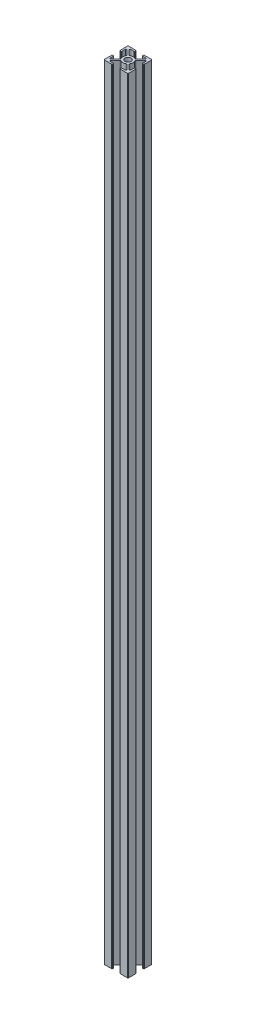
SolidWorks part; units mm, degrees
ref_plane "Front Plane" through (0, 0, 0) normal (0, 0, 1) x (1, 0, 0)
ref_plane "Top Plane" through (0, 0, 0) normal (0, 1, 0) x (1, 0, 0)
ref_plane "Right Plane" through (0, 0, 0) normal (1, 0, 0) x (0, 0, -1)
sketch "Sketch1" plane through (0, 0, 0) normal (0, 1, 0) x (1, 0, 0)
  point P0 (0, 0)
  line B0 (-6.2474, 8.6) -> (-3.6, 8.6)
  line B1 (-9.5, -10) -> (-3.6, -10)
  line B2 (-10, -9.5) -> (-10, -3.6)
  line B3 (-9.5, 10) -> (-3.6, 10)
  line B4 (10, -9.5) -> (10, -3.6)
  line B5 (8.6, -6.2474) -> (8.6, -3.6)
  line B6 (-6.2474, -8.6) -> (-3.6, -8.6)
  line B7 (-8.6, -6.2474) -> (-8.6, -3.6)
  line B8 (-7.7464, 6.7565) -> (-3.7448, 2.7548)
  line B9 (-6.6465, 7.6365) -> (-2.7548, 3.7448)
  line B10 (6.6465, 7.6365) -> (2.7548, 3.7448)
  line B11 (7.6365, 6.6465) -> (3.7448, 2.7548)
  line B12 (7.6365, -6.6465) -> (3.7448, -2.7548)
  line B13 (6.6465, -7.6365) -> (2.7548, -3.7448)
  line B14 (-6.6465, -7.6365) -> (-2.7548, -3.7448)
  line B15 (-7.6365, -6.6465) -> (-3.7448, -2.7548)
  line B16 (-8.6, 6.4029) -> (-8.6, 3.6)
  line B17 (6.2474, -8.6) -> (3.6, -8.6)
  line B18 (-9, 3.2) -> (-9.6, 3.2)
  line B19 (-9.6, -3.2) -> (-9, -3.2)
  line B20 (9, 3.2) -> (9.6, 3.2)
  line B21 (9, -3.2) -> (9.6, -3.2)
  line B22 (-10, 3.6) -> (-10, 9.5)
  line B23 (10, 3.6) -> (10, 9.5)
  line B24 (8.6, 3.6) -> (8.6, 6.2474)
  line B25 (-3.2, 9.6) -> (-3.2, 9)
  line B26 (3.2, 9.6) -> (3.2, 9)
  line B27 (-3.2, -9.6) -> (-3.2, -9)
  line B28 (3.2, -9.6) -> (3.2, -9)
  line B29 (3.6, -10) -> (9.5, -10)
  line B30 (3.6, 10) -> (9.5, 10)
  line B31 (3.6, 8.6) -> (6.2474, 8.6)
  circle B32 centre (0, 0) radius 2.5
  arc B33 (-3.6669, 2.1485) -> (-3.6669, -2.1485) centre (0, 0) ccw
  arc B34 (2.1485, 3.6669) -> (-2.1485, 3.6669) centre (0, 0) ccw
  arc B35 (3.6669, -2.1485) -> (3.6669, 2.1485) centre (0, 0) ccw
  arc B36 (-2.1485, -3.6669) -> (2.1485, -3.6669) centre (0, 0) ccw
  arc B37 (-10, -9.5) -> (-9.5, -10) centre (-9.5, -9.5) ccw
  arc B38 (9.5, -10) -> (10, -9.5) centre (9.5, -9.5) ccw
  arc B39 (10, 9.5) -> (9.5, 10) centre (9.5, 9.5) ccw
  arc B40 (-9.5, 10) -> (-10, 9.5) centre (-9.5, 9.5) ccw
  arc B41 (-7.7464, 6.7565) -> (-8.6, 6.4029) centre (-8.1, 6.4029) ccw
  arc B42 (-6.2474, -8.6) -> (-6.6465, -7.6365) centre (-6.2474, -8.0356) cw
  arc B43 (-8.6, -6.2474) -> (-7.6365, -6.6465) centre (-8.0356, -6.2474) ccw
  arc B44 (6.2474, -8.6) -> (6.6465, -7.6365) centre (6.2474, -8.0356) ccw
  arc B45 (7.6365, -6.6465) -> (8.6, -6.2474) centre (8.0356, -6.2474) ccw
  arc B46 (8.6, 6.2474) -> (7.6365, 6.6465) centre (8.0356, 6.2474) ccw
  arc B47 (6.6465, 7.6365) -> (6.2474, 8.6) centre (6.2474, 8.0356) ccw
  arc B48 (-6.2474, 8.6) -> (-6.6465, 7.6365) centre (-6.2474, 8.0356) ccw
  arc B49 (2.7548, 3.7448) -> (2.1485, 3.6669) centre (2.4013, 4.0983) cw
  arc B50 (3.7448, 2.7548) -> (3.6669, 2.1485) centre (4.0983, 2.4013) ccw
  arc B51 (3.7448, -2.7548) -> (3.6669, -2.1485) centre (4.0983, -2.4013) cw
  arc B52 (2.7548, -3.7448) -> (2.1485, -3.6669) centre (2.4013, -4.0983) ccw
  arc B53 (-2.1485, -3.6669) -> (-2.7548, -3.7448) centre (-2.4013, -4.0983) ccw
  arc B54 (-3.7448, -2.7548) -> (-3.6669, -2.1485) centre (-4.0983, -2.4013) ccw
  arc B55 (-3.7448, 2.7548) -> (-3.6669, 2.1485) centre (-4.0983, 2.4013) cw
  arc B56 (-2.1485, 3.6669) -> (-2.7548, 3.7448) centre (-2.4013, 4.0983) cw
  arc B57 (-3.2, 9) -> (-3.6, 8.6) centre (-3.6, 9) cw
  arc B58 (-3.2, 9.6) -> (-3.6, 10) centre (-3.6, 9.6) ccw
  arc B59 (3.2, 9.6) -> (3.6, 10) centre (3.6, 9.6) cw
  arc B60 (3.2, 9) -> (3.6, 8.6) centre (3.6, 9) ccw
  arc B61 (9.6, 3.2) -> (10, 3.6) centre (9.6, 3.6) ccw
  arc B62 (9, 3.2) -> (8.6, 3.6) centre (9, 3.6) cw
  arc B63 (9.6, -3.2) -> (10, -3.6) centre (9.6, -3.6) cw
  arc B64 (9, -3.2) -> (8.6, -3.6) centre (9, -3.6) ccw
  arc B65 (3.2, -9) -> (3.6, -8.6) centre (3.6, -9) cw
  arc B66 (3.2, -9.6) -> (3.6, -10) centre (3.6, -9.6) ccw
  arc B67 (-3.2, -9.6) -> (-3.6, -10) centre (-3.6, -9.6) cw
  arc B68 (-3.2, -9) -> (-3.6, -8.6) centre (-3.6, -9) ccw
  arc B69 (-9, -3.2) -> (-8.6, -3.6) centre (-9, -3.6) cw
  arc B70 (-9.6, -3.2) -> (-10, -3.6) centre (-9.6, -3.6) ccw
  arc B71 (-9, 3.2) -> (-8.6, 3.6) centre (-9, 3.6) ccw
  arc B72 (-9.6, 3.2) -> (-10, 3.6) centre (-9.6, 3.6) cw
sketch_block_instance "2X2-1"
sketch_block "2X2" parameters "D4"=2.5, "D5"=4.25, "D10"=0.5, "D12"=0.5, "D13"=0.5644, "D14"=0.5, "D15"=0.4, "D1"=20, "D2"=1.4, "D3"=1.4, "D6"=6.4, "D7"=0.7, "D8"=1.4, "D9"=20, "D11"=6.4, "D16"=1.4
extrude "Boss-Extrude1" add sketch "Sketch1" along normal blind 650
